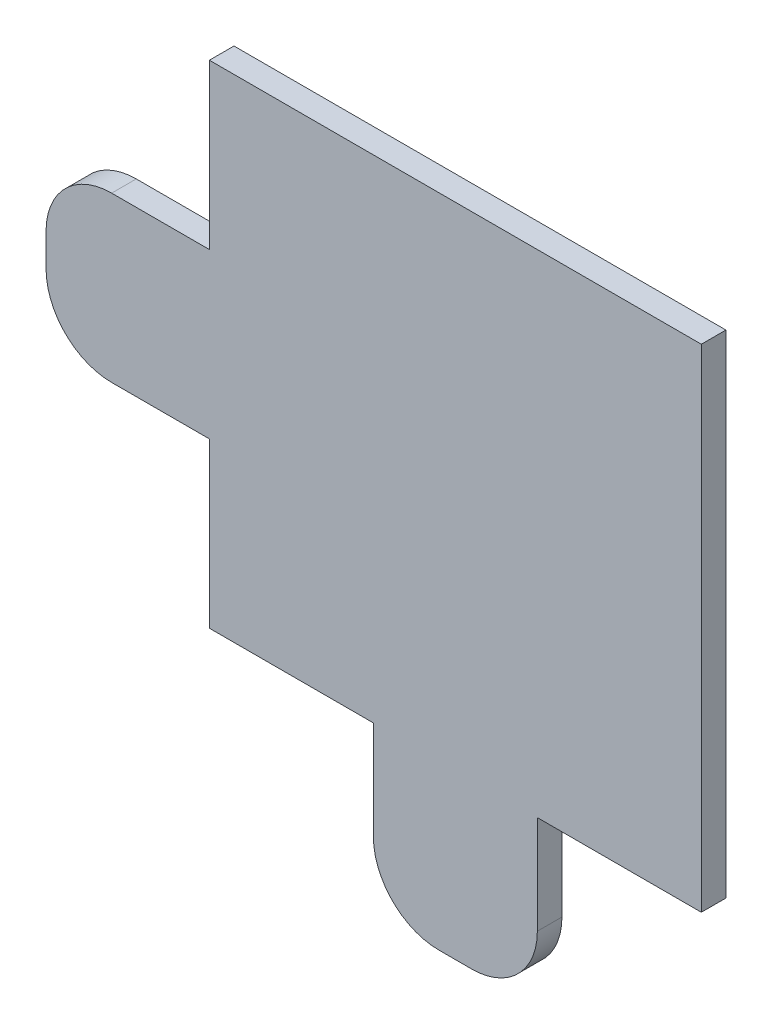
SolidWorks part; units mm, degrees
ref_plane "Front Plane" through (0, 0, 0) normal (0, 0, 1) x (1, 0, 0)
ref_plane "Top Plane" through (0, 0, 0) normal (0, 1, 0) x (1, 0, 0)
ref_plane "Right Plane" through (0, 0, 0) normal (1, 0, 0) x (0, 0, -1)
sketch "Sketch1" plane through (0, 0, 0) normal (0, 0, 1) x (1, 0, 0)
  line L0 (-0.4192, 0.1) -> (-0.3, 0.1)
  line L1 (-0.3, 0.3) -> (0.3, 0.3)
  line L2 (-0.3, 0.3) -> (-0.3, 0.1)
  line L3 (-0.3, -0.3) -> (-0.1, -0.3)
  line L4 (0.3, 0.3) -> (0.3, -0.3)
  line L5 (-0.3, 0.3) -> (0.3, -0.3) construction
  line L6 (-0.3, -0.3) -> (0.3, 0.3) construction
  line L7 (-0.4192, -0.1) -> (-0.3, -0.1)
  line L8 (-0.1, -0.42) -> (-0.1, -0.3)
  line L9 (0.1, -0.42) -> (0.1, -0.3)
  line L10 (-0.4992, 0.02) -> (-0.4992, -0.02)
  line L11 (0.1, -0.3) -> (0.3, -0.3)
  line L12 (-0.3, -0.1) -> (-0.3, -0.3)
  line L15 (-0.02, -0.5) -> (0.02, -0.5)
  arc A0 (-0.4992, 0.02) -> (-0.4192, 0.1) centre (-0.4192, 0.02) cw
  arc A1 (-0.4192, -0.1) -> (-0.4992, -0.02) centre (-0.4192, -0.02) cw
  arc A5 (0.1, -0.42) -> (0.02, -0.5) centre (0.02, -0.42) cw
  arc A6 (-0.02, -0.5) -> (-0.1, -0.42) centre (-0.02, -0.42) cw
  point P0 (0, 0)
  point P5 (-0.3, 0)
  point P8 (-0.4992, 0)
  point P9 (0, -0.5)
  point P11 (0, -0.3)
  point P33 (-0.4992, 0.1)
  point P49 (0.1, -0.5)
  dimension "D8" = 0.08
  dimension "D9" = 0.08
  dimension "D12" = 0.08
  dimension "D1" = 0.6
  dimension "D2" = 0.6
  dimension "D5" = 0.1992
  dimension "D6" = 0.2
extrude "Boss-Extrude2" add sketch "Sketch1" along normal mid plane 0.03
